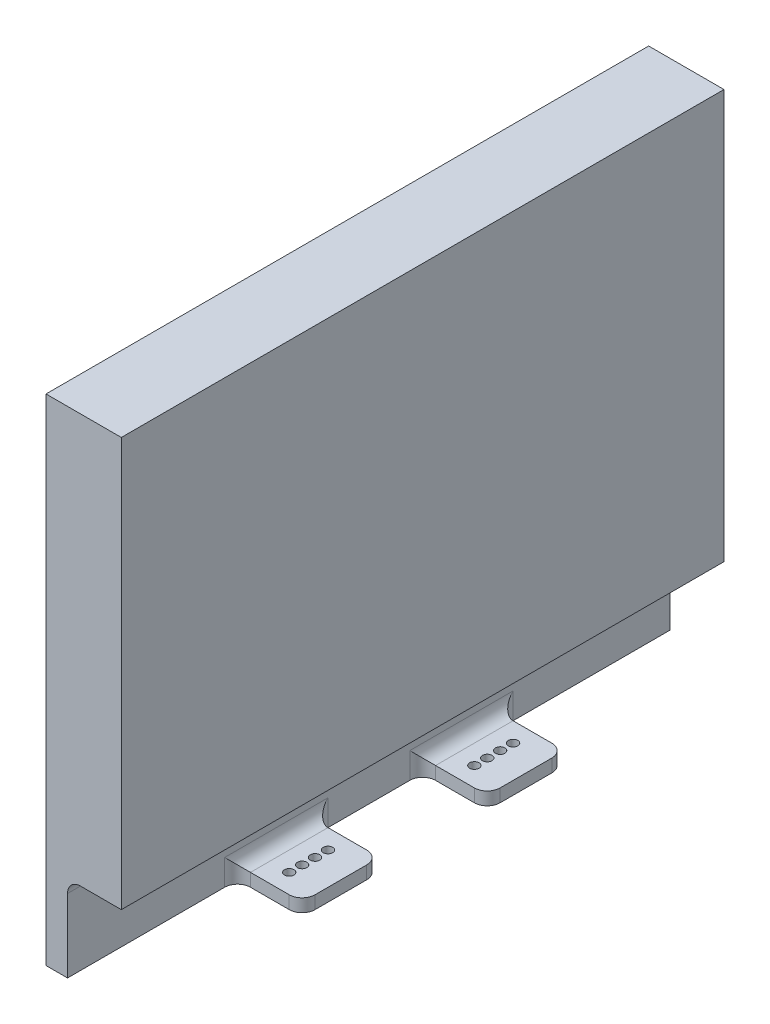
SolidWorks part; units mm, degrees
ref_plane "Front Plane" through (0, 0, 0) normal (0, 0, 1) x (1, 0, 0)
ref_plane "Top Plane" through (0, 0, 0) normal (0, 1, 0) x (1, 0, 0)
ref_plane "Right Plane" through (0, 0, 0) normal (1, 0, 0) x (0, 0, -1)
sketch "Sketch1" plane through (0, 0, 0) normal (0, 1, 0) x (1, 0, 0)
  circle A0 centre (0, 0) radius 10
  dimension "D1" = 20
extrude "Boss-Extrude1" add sketch "Sketch1" along normal blind 3
sketch "Sketch2" plane through (0, 3, 0) normal (0, 1, 0) x (1, 0, 0)
  circle A0 centre (0, 0) radius 5
  dimension "D1" = 10
extrude "Boss-Extrude2" add sketch "Sketch2" along normal blind 100
sketch "Sketch3" plane through (0, 0, 0) normal (0, -1, 0) x (1, 0, 0)
  line L0 (-1.89, 1.6364) -> (-1.89, -1.6364)
  arc A0 (-1.89, 1.6364) -> (-1.9038, -1.6203) centre (0, 0) cw
  dimension "D1" = 2.5
  dimension "D2" = 2.5
extrude "Cut-Extrude1" cut sketch "Sketch3" against normal blind 15 contours A0 L0
sketch "Sketch4" plane through (0, 103, 0) normal (0, 1, 0) x (1, 0, 0)
  line L1 (-7, 50) -> (7, 50)
  line L2 (-7, 50) -> (-7, -50)
  line L3 (-7, -50) -> (7, -50)
  line L4 (7, 50) -> (7, -50)
  line L5 (-7, 50) -> (7, -50) construction
  line L6 (-7, -50) -> (7, 50) construction
  point P0 (0, 0)
  dimension "D1" = 14
  dimension "D2" = 100
extrude "Boss-Extrude3" add sketch "Sketch4" against normal blind 90
sketch "Sketch5" plane through (0, 3, 0) normal (0, 1, 0) x (1, 0, 0)
  circle A0 centre (0, 0) radius 10
extrude "Boss-Extrude4" add sketch "Sketch5" along normal blind 3 from offset 5
sketch "Sketch7" plane through (0, 0, 50) normal (0, 0, 1) x (1, 0, 0)
  line L1 (17.3621, 0) -> (-14.1764, 0)
  line L2 (17.3621, 0) -> (17.3621, 13)
  line L3 (17.3621, 13) -> (-14.1764, 13)
  line L4 (-14.1764, 0) -> (-14.1764, 13)
extrude "Cut-Extrude2" cut sketch "Sketch7" against normal blind 80
sketch "Sketch8" plane through (0, 0, 50) normal (0, 0, 1) x (1, 0, 0)
  line L0 (7, 13) -> (7, 103) construction
  line L1 (7, 16) -> (-2, 16)
  line L2 (7, 16) -> (7, 103)
  line L3 (7, 103) -> (-2, 103)
  line L4 (-2, 16) -> (-2, 103)
  line L5 (-7, 103) -> (7, 103) construction
  line L6 (-7, 13) -> (-7, 103) construction
  line L7 (-7, 13) -> (7, 13) construction
  dimension "D1" = 5
  dimension "D2" = 3
extrude "Cut-Extrude3" cut sketch "Sketch8" against normal blind 130
sketch "Sketch9" plane through (0, 16, 0) normal (0, 1, 0) x (1, 0, 0)
  line L0 (7, 50) -> (7, -50) construction
  line L1 (7, -12.5) -> (-2, -12.5)
  line L2 (7, -12.5) -> (7, 12.5)
  line L3 (7, 12.5) -> (-2, 12.5)
  line L4 (-2, -12.5) -> (-2, 12.5)
  line L5 (-2, 50) -> (-2, -50) construction
  line L6 (-2, -50) -> (7, -50) construction
  dimension "D1" = 25
  dimension "D2" = 37.5
extrude "Cut-Extrude4" cut sketch "Sketch9" against normal blind 80
sketch "Sketch10" plane through (7, 0, 0) normal (1, 0, 0) x (0, 0, -1)
  line L1 (-50, 13) -> (-12.5, 13)
  line L2 (-50, 13) -> (-50, 16)
  line L3 (-50, 16) -> (-12.5, 16)
  line L4 (-12.5, 13) -> (-12.5, 16)
  line L5 (12.5, 13) -> (50, 13)
  line L6 (12.5, 13) -> (12.5, 16)
  line L7 (12.5, 16) -> (50, 16)
  line L8 (50, 13) -> (50, 16)
extrude "Boss-Extrude5" add sketch "Sketch10" along normal blind 6
sketch "Sketch11" plane through (0, 16, 0) normal (0, 1, 0) x (1, 0, 0)
  line L0 (-2, -12.5) -> (13, -12.5) construction
  line L1 (5.5, -17) -> (5.5, 26) construction
  circle A0 centre (5.5, -17) radius 1.1
  circle A1 centre (5.5, -20) radius 1.1
  circle A2 centre (5.5, -23) radius 1.1
  circle A3 centre (5.5, -26) radius 1.1
  circle A4 centre (5.5, 26) radius 1.1
  circle A5 centre (5.5, 23) radius 1.1
  circle A6 centre (5.5, 20) radius 1.1
  circle A7 centre (5.5, 17) radius 1.1
  dimension "D1" = 4.5
  dimension "D2" = 2.2
  dimension "D3" = 3
  dimension "D4" = 2.2
  dimension "D5" = 3
  dimension "D6" = 2.2
  dimension "D7" = 3
  dimension "D8" = 2.2
  dimension "D10" = 43
  dimension "D9" = 2
extrude "Cut-Extrude5" cut sketch "Sketch11" against normal blind 56
sketch "Sketch14" plane through (0, 16, 0) normal (0, 1, 0) x (1, 0, 0)
  line L0 (-2, -12.5) -> (13, -12.5) construction
  line L1 (13, -50) -> (-2, -50)
  line L2 (13, -50) -> (13, -30.5)
  line L3 (13, -30.5) -> (-2, -30.5)
  line L4 (-2, -50) -> (-2, -30.5)
  line L5 (13, 50) -> (-2, 50)
  line L6 (13, 50) -> (13, 30.5)
  line L7 (13, 30.5) -> (-2, 30.5)
  line L8 (-2, 50) -> (-2, 30.5)
  dimension "D1" = 18
  dimension "D2" = 19.5
  dimension "D3" = 15
extrude "Cut-Extrude6" cut sketch "Sketch14" against normal blind 56
fillet "Fillet1" radius 3 10 edges at (13, 14.5, -30.5) (-2, 14.5, -30.5) (13, 14.5, -12.5) (-2, 14.5, -12.5) (-2, 14.5, 12.5) (-2, 14.5, 30.5) (13, 14.5, 12.5) (13, 14.5, 30.5) (-2, 16, -21.5) (-2, 16, 21.5)
ref_plane "Plane1" through (-2, 103, -50) normal (0, 0, 1) x (1, 0, 0)
sketch "Sketch19" plane through (0, 103, 0) normal (0, 1, 0) x (1, 0, 0)
  line L1 (-2, 50) -> (-7, 50)
  line L2 (-2, 50) -> (-2, -50)
  line L3 (-2, -50) -> (-7, -50)
  line L4 (-7, 50) -> (-7, -50)
extrude "Boss-Extrude6" add sketch "Sketch19" along normal blind 25
sketch "Sketch22" plane through (0, 0, 50) normal (0, 0, 1) x (1, 0, 0)
  line L1 (-7, 13) -> (-2, 13)
  line L2 (-7, 13) -> (-7, 128)
  line L3 (-7, 128) -> (-2, 128)
  line L4 (-2, 13) -> (-2, 128)
extrude "Boss-Extrude8" add sketch "Sketch22" along normal blind 20
sketch "Sketch23" plane through (0, 0, -50) normal (0, 0, -1) x (-1, 0, 0)
  line L1 (7, 128) -> (2, 128)
  line L2 (7, 128) -> (7, 13)
  line L3 (7, 13) -> (2, 13)
  line L4 (2, 128) -> (2, 13)
extrude "Boss-Extrude9" add sketch "Sketch23" along normal blind 20
sketch "Sketch24" plane through (-2, 0, 0) normal (1, 0, 0) x (0, 0, -1)
  line L0 (-70, 13) -> (-70, 128) construction
  line L1 (70, 128) -> (-70, 128)
  line L2 (70, 128) -> (70, 33)
  line L3 (70, 33) -> (-70, 33)
  line L4 (-70, 128) -> (-70, 33)
  dimension "D1" = 95
extrude "Boss-Extrude10" add sketch "Sketch24" along normal blind 15
sketch "Sketch25" plane through (-7, 0, 0) normal (-1, 0, 0) x (0, 0, 1)
  line L0 (-70, 13) -> (-70, 128) construction
  line L1 (-65, 125.5) -> (65, 125.5)
  line L2 (-65, 125.5) -> (-65, 35.5)
  line L3 (-65, 35.5) -> (65, 35.5)
  line L4 (65, 125.5) -> (65, 35.5)
  line L5 (-70, 128) -> (70, 128) construction
  dimension "D1" = 90
  dimension "D2" = 130
  dimension "D3" = 5
  dimension "D4" = 2.5
extrude "Cut-Extrude7" cut sketch "Sketch25" against normal blind 10
fillet "Fillet2" radius 3 1 edges at (-2, 33, 0)
sketch "Sketch26" plane through (0, 0, 70) normal (0, 0, 1) x (1, 0, 0)
  line L0 (13, 128) -> (-7, 128) construction
  line L1 (13, 33) -> (10.5, 33)
  line L2 (13, 33) -> (13, 128)
  line L3 (13, 128) -> (10.5, 128)
  line L4 (10.5, 33) -> (10.5, 128)
  dimension "D1" = 2.5
extrude "Cut-Extrude8" cut sketch "Sketch26" against normal blind 130
sketch "Sketch27" plane through (0, 128, 0) normal (0, 1, 0) x (1, 0, 0)
  line L1 (13, 70) -> (10.5, 70)
  line L2 (13, 70) -> (13, 60)
  line L3 (13, 60) -> (10.5, 60)
  line L4 (10.5, 70) -> (10.5, 60)
extrude "Cut-Extrude9" cut sketch "Sketch27" against normal through all
